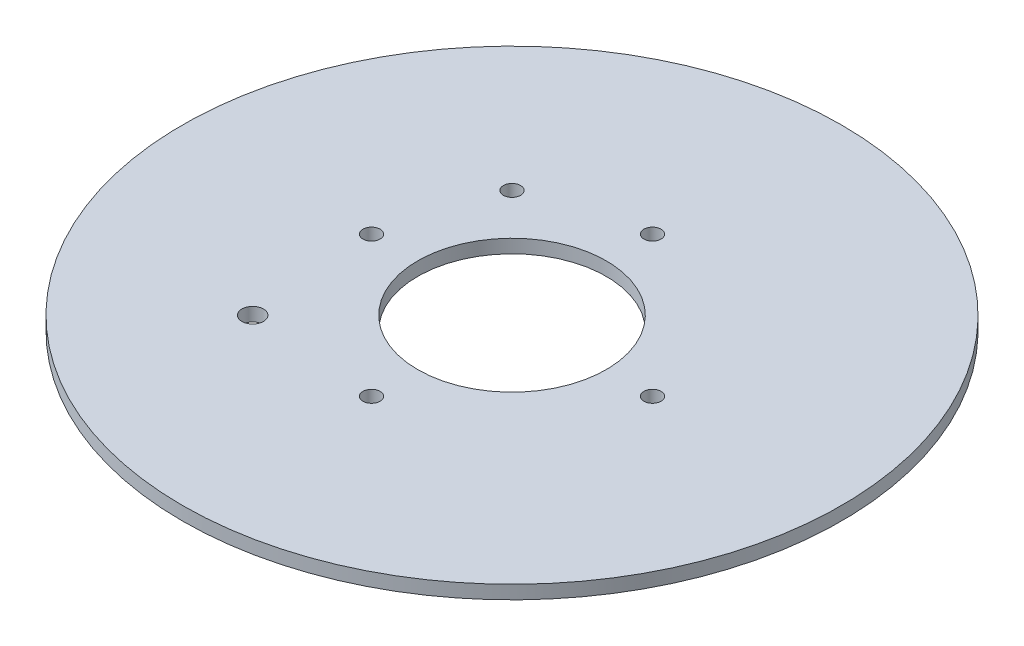
SolidWorks part; units mm, degrees
material "Acrylic (Medium-high impact)"
ref_plane "Front" through (0, 0, 0) normal (0, 0, 1) x (1, 0, 0)
ref_plane "Top" through (0, 0, 0) normal (0, 1, 0) x (1, 0, 0)
ref_plane "Right" through (0, 0, 0) normal (1, 0, 0) x (0, 0, -1)
sketch "Sketch1" plane through (0, 0, 0) normal (0, 1, 0) x (1, 0, 0)
  circle A0 centre (0, 0) radius 77.46
  dimension "D1" = 154.92
extrude "Boss-Extrude1" add sketch "Sketch1" along normal blind 3.175
sketch "Sketch24" plane through (0, 3.175, 0) normal (0, 1, 0) x (1, 0, 0)
  circle A0 centre (0, 0) radius 22.1615
  circle A1 centre (0, 0) radius 33.02 construction
  circle A2 centre (-30.48, -30.48) radius 2.54
  circle A3 centre (0, -33.02) radius 2.0193
  circle A4 centre (33.02, 0) radius 2.0193
  circle A5 centre (0, 33.02) radius 2.0193
  circle A6 centre (-33.02, 0) radius 2.0193
  circle A7 centre (-25.4, 25.4) radius 2.0193
  dimension "D1" = 33.02
  dimension "D2" = 4.0386
  dimension "D3" = 44.323
  dimension "D8" = 5.08
  dimension "D4" = 25.4
  dimension "D5" = 25.4
  dimension "D6" = 30.48
  dimension "D7" = 30.48
extrude "Cut-Extrude14" cut sketch "Sketch24" against normal through all
